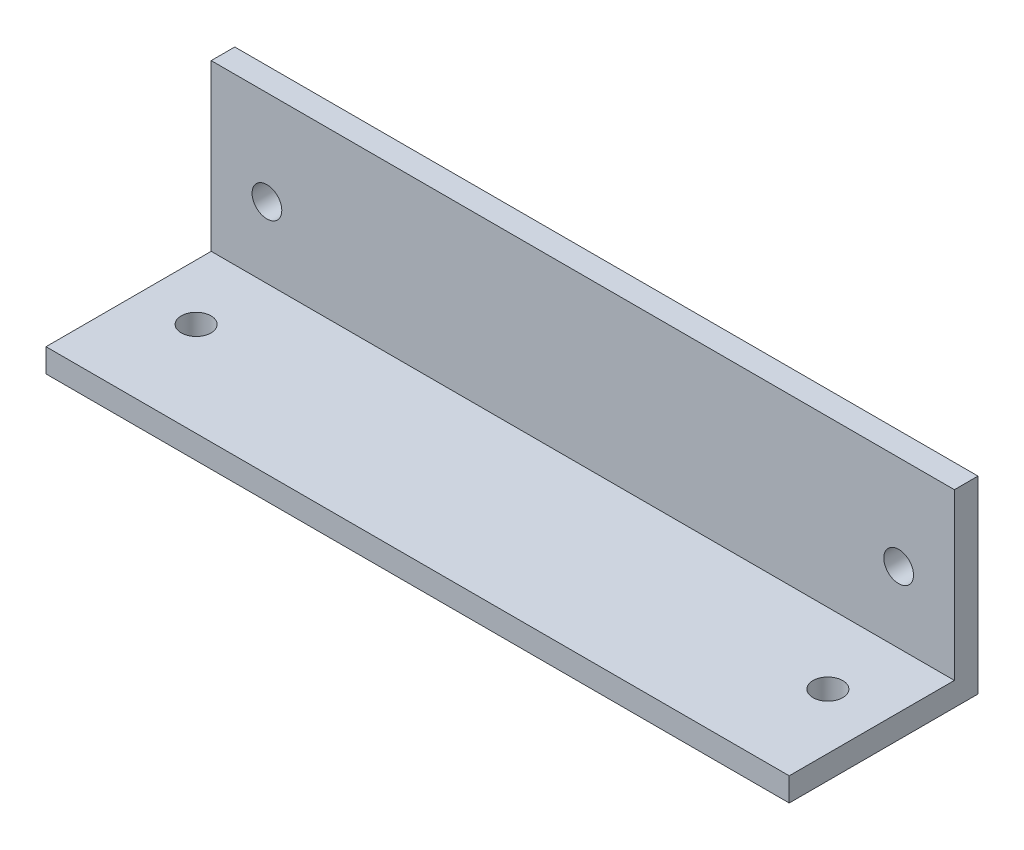
SolidWorks part; units mm, degrees
ref_plane "Front Plane" through (0, 0, 0) normal (0, 0, 1) x (1, 0, 0)
ref_plane "Top Plane" through (0, 0, 0) normal (0, 1, 0) x (1, 0, 0)
ref_plane "Right Plane" through (0, 0, 0) normal (1, 0, 0) x (0, 0, -1)
sketch "Sketch1" plane through (0, 0, 0) normal (1, 0, 0) x (0, 0, -1)
  line L0 (0, 50.8) -> (0, 0)
  line L1 (0, 0) -> (-50.8, 0)
  line L2 (-50.8, 0) -> (-50.8, 6.35)
  line L3 (-50.8, 6.35) -> (-6.35, 6.35)
  line L4 (-6.35, 6.35) -> (-6.35, 50.8)
  line L5 (-6.35, 50.8) -> (0, 50.8)
  dimension "D1" = 50.8
  dimension "D2" = 6.35
  dimension "D3" = 50.8
extrude "Boss-Extrude1" add sketch "Sketch1" along normal mid plane 200
sketch "Sketch2" plane through (0, 0, 0) normal (0, -1, 0) x (1, 0, 0)
  line L0 (-100, 25.4) -> (100, 25.4) construction
  line L1 (-100, 50.8) -> (-100, 0) construction
  line L2 (100, 50.8) -> (100, 0) construction
  line L3 (0, 50.8) -> (0, 0) construction
  line L4 (100, 50.8) -> (-100, 50.8) construction
  circle A0 centre (-85, 25.4) radius 4
  circle A1 centre (85, 25.4) radius 4
  dimension "D1" = 8
  dimension "D2" = 15
extrude "Cut-Extrude1" cut sketch "Sketch2" against normal up to next
ref_plane "Plane1" through (0, 0, 0) normal (0, -0.7071, 0.7071) x (-1, 0, 0)
mirror "Mirror1" about plane through (0, 0, 0) normal (0, -0.7071, 0.7071) of "Cut-Extrude1"
